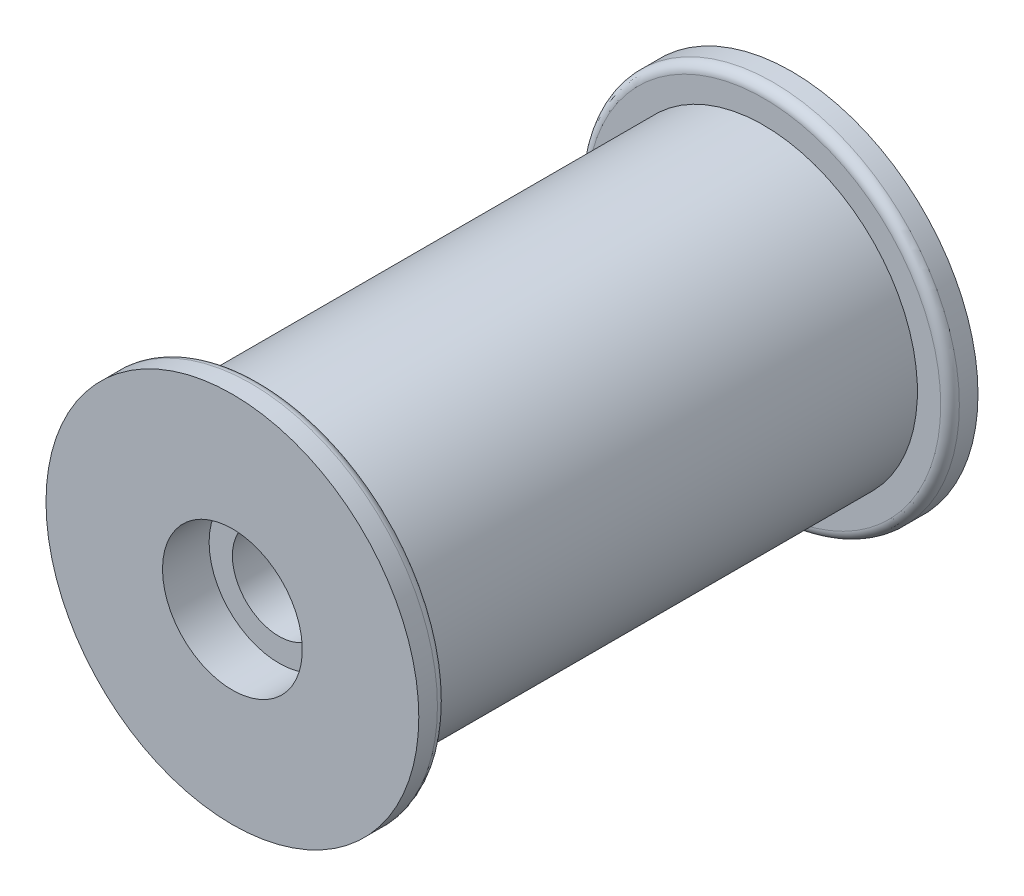
SolidWorks part; units mm, degrees
material "ABS"
ref_plane "前视基准面" through (0, 0, 0) normal (0, 0, 1) x (1, 0, 0)
ref_plane "上视基准面" through (0, 0, 0) normal (0, 1, 0) x (1, 0, 0)
ref_plane "右视基准面" through (0, 0, 0) normal (1, 0, 0) x (0, 0, -1)
other "Configuration Table"
sketch "草图1" plane through (0, 0, 0) normal (0, 1, 0) x (1, 0, 0)
  line L0 (0, 0) -> (0, -60) construction
  line L1 (0, -60) -> (20, -60)
  line L2 (20, -60) -> (20, -57)
  line L3 (20, -57) -> (16.5, -57)
  line L4 (16.5, -57) -> (16.5, -3)
  line L5 (16.5, -3) -> (20, -3)
  line L6 (20, -3) -> (20, 0)
  line L7 (20, 0) -> (0, 0)
  line L8 (7.5, 0) -> (7.5, -5)
  line L9 (7.5, -5) -> (5, -5)
  line L10 (5, -5) -> (5, -55)
  line L11 (5, -55) -> (7.5, -55)
  line L12 (7.5, -55) -> (7.5, -60)
  dimension "D1" = 60
  dimension "D2" = 3
  dimension "D3" = 3
  dimension "D4" = 20
  dimension "D5" = 16.5
  dimension "D6" = 15
  dimension "D7" = 10
  dimension "D8" = 5
  dimension "D9" = 5
  dimension "D10" = 15
revolve "旋转1" add sketch "草图1" angle 360 about L0
fillet "圆角2" radius 1 2 edges at (-20, 0, 57) (-20, 0, 3)
